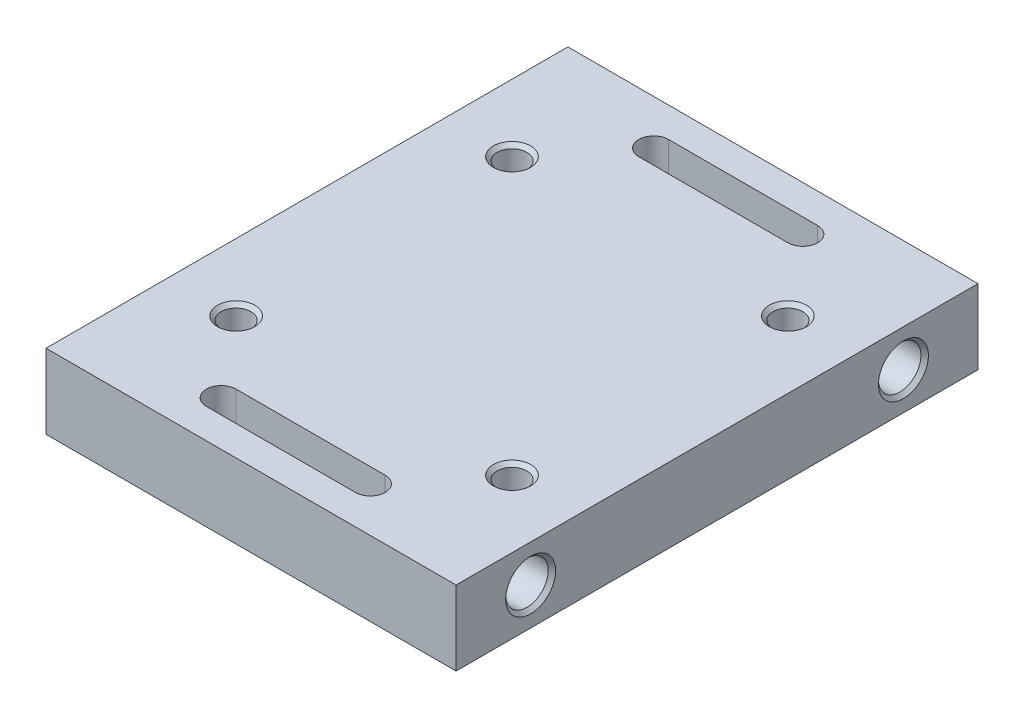
SolidWorks part; units mm, degrees
material "ABS PC"
ref_plane "Front Plane" through (0, 0, 0) normal (0, 0, 1) x (1, 0, 0)
ref_plane "Top Plane" through (0, 0, 0) normal (0, 1, 0) x (1, 0, 0)
ref_plane "Right Plane" through (0, 0, 0) normal (1, 0, 0) x (0, 0, -1)
sketch "Sketch1" plane through (0, 0, 0) normal (0, 1, 0) x (1, 0, 0)
  line L0 (-18.5, 18.5) -> (18.5, 18.5) construction
  line L1 (-27.5, 35) -> (27.5, 35)
  line L2 (-27.5, 35) -> (-27.5, -35)
  line L3 (-27.5, -35) -> (27.5, -35)
  line L4 (27.5, 35) -> (27.5, -35)
  line L5 (-27.5, 35) -> (27.5, -35) construction
  line L6 (-27.5, -35) -> (27.5, 35) construction
  line L7 (18.5, 18.5) -> (18.5, -18.5) construction
  line L8 (18.5, -18.5) -> (-18.5, -18.5) construction
  line L9 (-18.5, -18.5) -> (-18.5, 18.5) construction
  line L10 (-10, 27) -> (10, 27)
  line L11 (-10, 31) -> (10, 31)
  line L12 (-9.4729, 0) -> (9.6551, 0) construction
  line L13 (-10, -31) -> (10, -31)
  line L14 (-10, -27) -> (10, -27)
  circle A0 centre (18.5, -18.5) radius 2
  circle A1 centre (-18.5, -18.5) radius 2
  circle A2 centre (18.5, 18.5) radius 2
  circle A3 centre (-18.5, 18.5) radius 2
  arc A4 (-10, 27) -> (-10, 31) centre (-10, 29) cw
  arc A5 (10, 31) -> (10, 27) centre (10, 29) cw
  arc A6 (10, -31) -> (10, -27) centre (10, -29) ccw
  arc A7 (-10, -27) -> (-10, -31) centre (-10, -29) ccw
  point P0 (0, 0)
  point P15 (18.5, 0)
  point P16 (0, -18.5)
  point P34 (0, 27)
  dimension "D5" = 4
  dimension "D6" = 2
  dimension "D7" = 6
  dimension "D1" = 70
  dimension "D2" = 55
  dimension "D3" = 37
  dimension "D4" = 37
  dimension "D8" = 20
extrude "Boss-Extrude1" add sketch "Sketch1" along normal mid plane 10
sketch "Sketch2" plane through (27.5, 0, 0) normal (1, 0, 0) x (0, 0, -1)
  line L0 (0, -1.812) -> (0, 3.1167) construction
  circle A0 centre (-25, 0) radius 2.85
  circle A1 centre (25, 0) radius 2.85
  dimension "D1" = 25
  dimension "D2" = 5.7
extrude "Cut-Extrude1" cut sketch "Sketch2" against normal blind 8
mirror "Mirror1" about plane through (0, 0, 0) normal (1, 0, 0) of "Cut-Extrude1"
chamfer "Chamfer1" distance 0.5 angle 45 8 edges at (-27.5, 0, -22.15) (-27.5, 0, 22.15) (27.5, 0, -22.15) (27.5, 0, 22.15) (-18.5, 5, 20.5) (18.5, 5, 20.5) (18.5, 5, -16.5) (-18.5, 5, -16.5)
